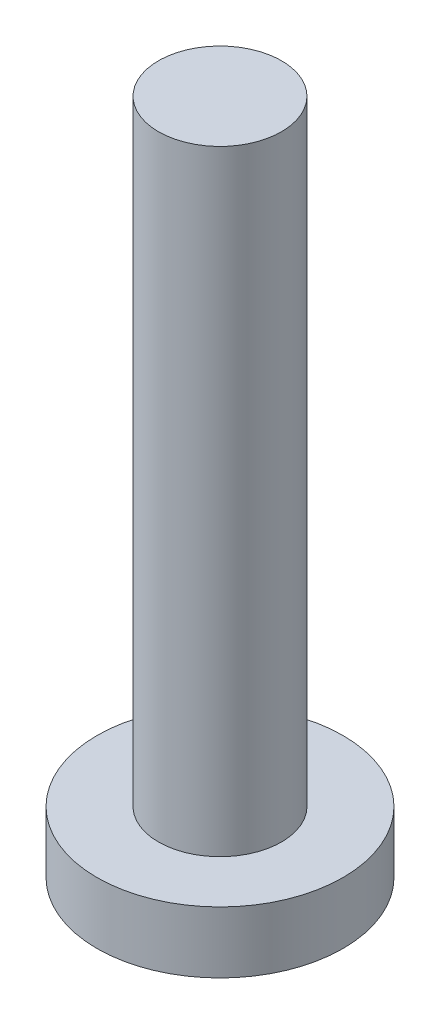
SolidWorks part; units mm, degrees
ref_plane "Front" through (0, 0, 0) normal (0, 0, 1) x (1, 0, 0)
ref_plane "Top" through (0, 0, 0) normal (0, 1, 0) x (1, 0, 0)
ref_plane "Right" through (0, 0, 0) normal (1, 0, 0) x (0, 0, -1)
sketch "Skizze1" plane through (0, 0, 0) normal (0, 1, 0) x (1, 0, 0)
  circle A0 centre (0, 0) radius 10
  dimension "D1" = 20
extrude "Aufsatz-Linear austragen1" add sketch "Skizze1" along normal blind 5
sketch "Skizze2" plane through (0, 5, 0) normal (0, 1, 0) x (1, 0, 0)
  circle A0 centre (0, 0) radius 5
  dimension "D1" = 10
extrude "Aufsatz-Linear austragen2" add sketch "Skizze2" along normal blind 50
cosmetic thread "Gewindedarstellung1" parameters "D2"=9
